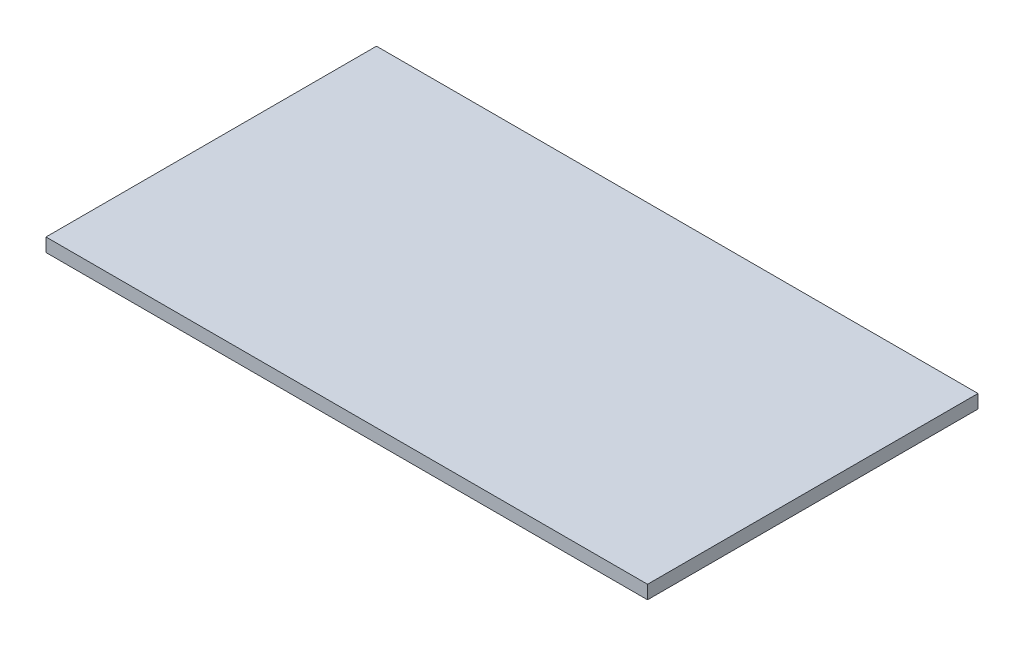
SolidWorks part; units mm, degrees
ref_plane "Front Plane" through (0, 0, 0) normal (0, 0, 1) x (1, 0, 0)
ref_plane "Top Plane" through (0, 0, 0) normal (0, 1, 0) x (1, 0, 0)
ref_plane "Right Plane" through (0, 0, 0) normal (1, 0, 0) x (0, 0, -1)
sketch "Sketch1" plane through (0, 0, 0) normal (0, 1, 0) x (1, 0, 0)
  line L1 (-354.9818, 36.9171) -> (154.7657, 36.9171)
  line L2 (-354.9818, 36.9171) -> (-354.9818, -243.1306)
  line L3 (-354.9818, -243.1306) -> (154.7657, -243.1306)
  line L4 (154.7657, 36.9171) -> (154.7657, -243.1306)
  dimension "D1" = 509.7475
  dimension "D2" = 280.0477
extrude "Boss-Extrude1" add sketch "Sketch1" along normal blind 11.43
equation "\"D2@Sketch1\"=\"Base Width@Assembled Container.Assembly\""
equation "\"D1@Sketch1\"=\"Base Length@Assembled Container.Assembly\""
equation "\"D1@Boss-Extrude1\"=\"Acrylic Thickness@Assembled Container.Assembly\""
